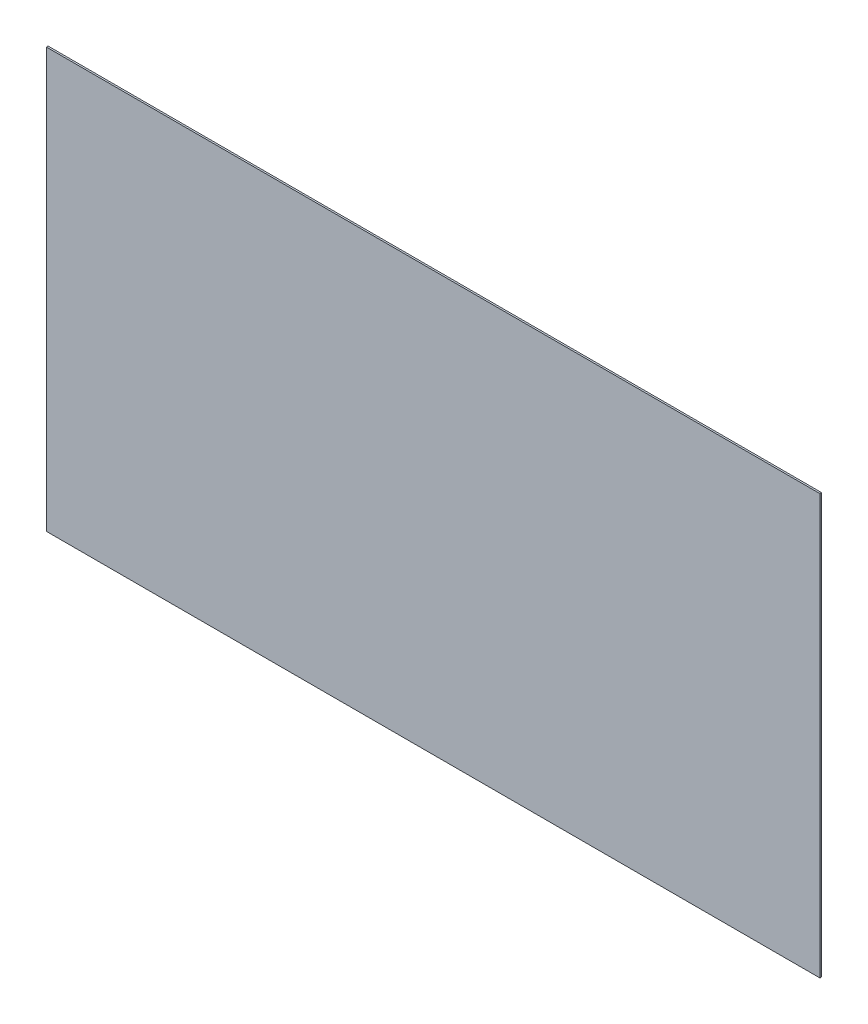
SolidWorks part; units mm, degrees
material "1345 Alloy"
ref_plane "Front Plane" through (0, 0, 0) normal (0, 0, 1) x (1, 0, 0)
ref_plane "Top Plane" through (0, 0, 0) normal (0, 1, 0) x (1, 0, 0)
ref_plane "Right Plane" through (0, 0, 0) normal (1, 0, 0) x (0, 0, -1)
sketch "Sketch1" plane through (0, 0, 0) normal (0, 0, 1) x (1, 0, 0)
  line L1 (-225, 122) -> (225, 122)
  line L2 (-225, 122) -> (-225, -122)
  line L3 (-225, -122) -> (225, -122)
  line L4 (225, 122) -> (225, -122)
  line L5 (-225, 122) -> (225, -122) construction
  line L6 (-225, -122) -> (225, 122) construction
  point P0 (0, 0)
  dimension "D1" = 450
  dimension "D2" = 244
extrude "Boss-Extrude1" add sketch "Sketch1" along normal blind 1
